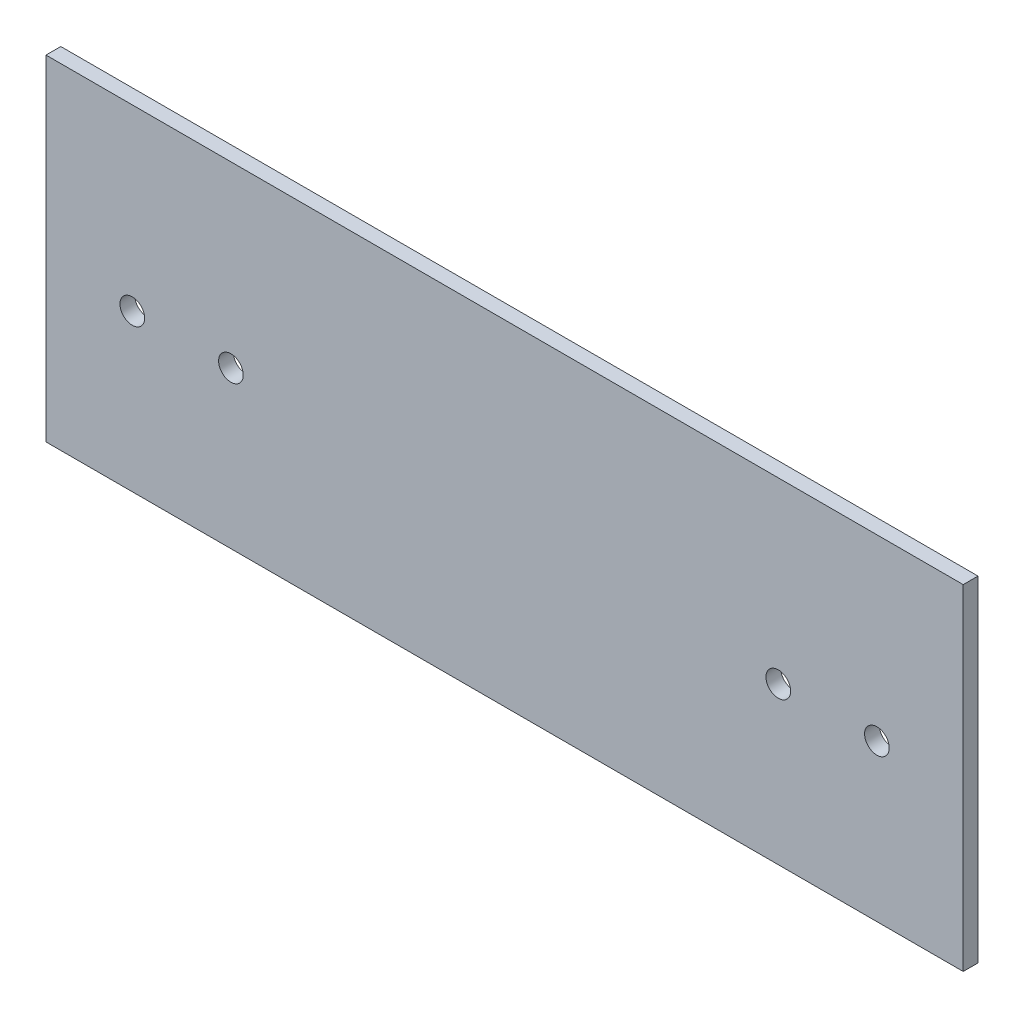
SolidWorks part; units mm, degrees
ref_plane "Front Plane" through (0, 0, 0) normal (0, 0, 1) x (1, 0, 0)
ref_plane "Top Plane" through (0, 0, 0) normal (0, 1, 0) x (1, 0, 0)
ref_plane "Right Plane" through (0, 0, 0) normal (1, 0, 0) x (0, 0, -1)
sketch "Esquisse1" plane through (0, 0, 0) normal (0, 0, 1) x (1, 0, 0)
  line L1 (-183, 52.0515) -> (-120, 52.0515)
  line L2 (-183, 52.0515) -> (-183, 120)
  line L3 (-183, 120) -> (3, 120)
  line L4 (3, 52.0515) -> (3, 120)
  line L9 (-60, 52.0515) -> (3, 52.0515)
  line L10 (-120, 52.0515) -> (-60, 52.0515)
  circle A0 centre (-165.5, 83.79) radius 2.5
  circle A4 centre (-145.5, 83.79) radius 2.5
  circle A5 centre (-145.5, 83.79) radius 2.5 construction
  circle A7 centre (-34.5, 83.79) radius 2.5
  circle A8 centre (-14.5, 83.79) radius 2.5
  circle A9 centre (-34.5, 83.79) radius 2.5 construction
  dimension "D3" = 5
  dimension "D4" = 5
extrude "Boss.-Extru.1" add sketch "Esquisse1" along normal blind 3
